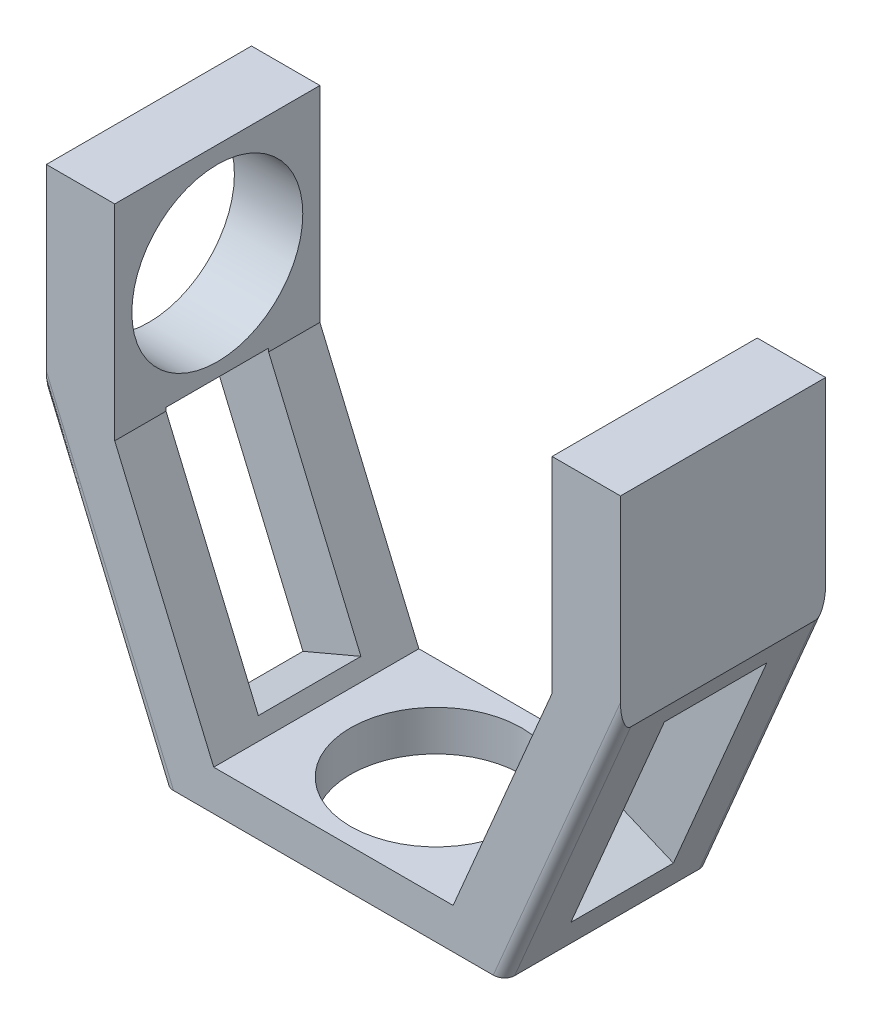
SolidWorks part; units mm, degrees
ref_plane "前视基准面" through (0, 0, 0) normal (0, 0, 1) x (1, 0, 0)
ref_plane "上视基准面" through (0, 0, 0) normal (0, 1, 0) x (1, 0, 0)
ref_plane "右视基准面" through (0, 0, 0) normal (1, 0, 0) x (0, 0, -1)
sketch "草图1" plane through (0, 0, 0) normal (0, 0, 1) x (1, 0, 0)
  line L0 (-161.7841, 76.9673) -> (-161.7841, 16.9673)
  line L1 (-161.7841, 16.9673) -> (-127.8261, -63.0327)
  line L2 (-127.8261, -63.0327) -> (-27.8261, -63.0327)
  line L3 (-27.8261, -63.0327) -> (6.1319, 16.9673)
  line L4 (6.1319, 16.9673) -> (6.1319, 76.9673)
  line L5 (6.1319, 76.9673) -> (-161.7841, 76.9673)
  dimension "D1" = 60
  dimension "D2" = 80
  dimension "D3" = 100
  dimension "D4" = 80
  dimension "D5" = 113
  dimension "D6" = 113
extrude "凸台-拉伸2" add sketch "草图1" along normal blind 60 contours L5 L0 L1 L2 L3 L4
sketch "草图5" plane through (0, 0, 60) normal (0, 0, 1) x (1, 0, 0)
  line L0 (-141.7841, 76.9673) -> (-141.7841, 16.9673)
  line L1 (6.1319, 76.9673) -> (-161.7841, 76.9673) construction
  line L2 (-13.8681, 76.9673) -> (-13.8681, 16.9673)
  line L3 (-141.7841, 16.9673) -> (-112.8364, -51.2291)
  line L4 (-112.8364, -51.2291) -> (-42.8158, -51.2291)
  line L5 (-42.8158, -51.2291) -> (-13.8681, 16.9673)
  line L6 (-141.7841, 76.9673) -> (-13.8681, 76.9673)
  dimension "D1" = 60
  dimension "D2" = 60
  dimension "D3" = 20
  dimension "D4" = 20
  dimension "D5" = 113
  dimension "D6" = 113
extrude "切除-拉伸2" cut sketch "草图5" against normal through all
sketch "草图7" plane through (-161.7841, 0, 0) normal (-1, 0, 0) x (0, 0, 1)
  line L0 (60, 76.9673) -> (0, 76.9673) construction
  line L1 (60, 76.9673) -> (60, 16.9673) construction
  circle A0 centre (30, 46.9673) radius 25
  dimension "D1" = 30
  dimension "D2" = 30
extrude "切除-拉伸4" cut sketch "草图7" against normal blind 20
sketch "草图8" plane through (0, -51.2291, 0) normal (0, 1, 0) x (1, 0, 0)
  line L0 (-112.8364, 0) -> (-42.8158, 0) construction
  line L1 (-42.8158, 0) -> (-42.8158, -60) construction
  circle A0 centre (-77.8158, -30) radius 25
  dimension "D1" = 30
  dimension "D2" = 35
extrude "切除-拉伸5" cut sketch "草图8" against normal blind 20
sketch "草图9" plane through (-130.9818, -55.5985, 0) normal (-0.9205, -0.3907, 0) x (0, 0, 1)
  line L0 (15, 71.9237) -> (15, 1.9237)
  line L1 (15, 1.9237) -> (45, 1.9237)
  line L2 (45, 1.9237) -> (45, 71.9237)
  line L3 (45, 71.9237) -> (15, 71.9237)
  line L4 (60, 78.8325) -> (60, -8.0763) construction
  line L5 (60, -8.0763) -> (0, -8.0763) construction
  dimension "D1" = 30
  dimension "D2" = 15
  dimension "D3" = 10
  dimension "D4" = 70
extrude "切除-拉伸6" cut sketch "草图9" against normal blind 20
sketch "草图10" plane through (-0.9069, 0.385, 0) normal (0.9205, -0.3907, 0) x (0, 0, -1)
  line L0 (-44.4734, 11.1055) -> (-44.4734, -58.8945)
  line L1 (-44.4734, -58.8945) -> (-14.4734, -58.8945)
  line L2 (-14.4734, -58.8945) -> (-14.4734, 11.1055)
  line L3 (-14.4734, 11.1055) -> (-44.4734, 11.1055)
  line L4 (-60, 18.0144) -> (0, 18.0144) construction
  line L5 (-60, -68.8945) -> (0, -68.8945) construction
  dimension "D1" = 30
  dimension "D2" = 30
  dimension "D3" = 70
  dimension "D4" = 70
  dimension "D5" = 6.9088
  dimension "D6" = 10
extrude "切除-拉伸7" cut sketch "草图10" against normal blind 20
fillet "圆角1" radius 3 1 edges at (-144.8051, -23.0327, 0)
fillet "圆角2" radius 3 1 edges at (-144.8051, -23.0327, 60)
fillet "圆角3" radius 3 1 edges at (-10.8471, -23.0327, 60)
fillet "圆角4" radius 3 1 edges at (-10.8471, -23.0327, 0)
